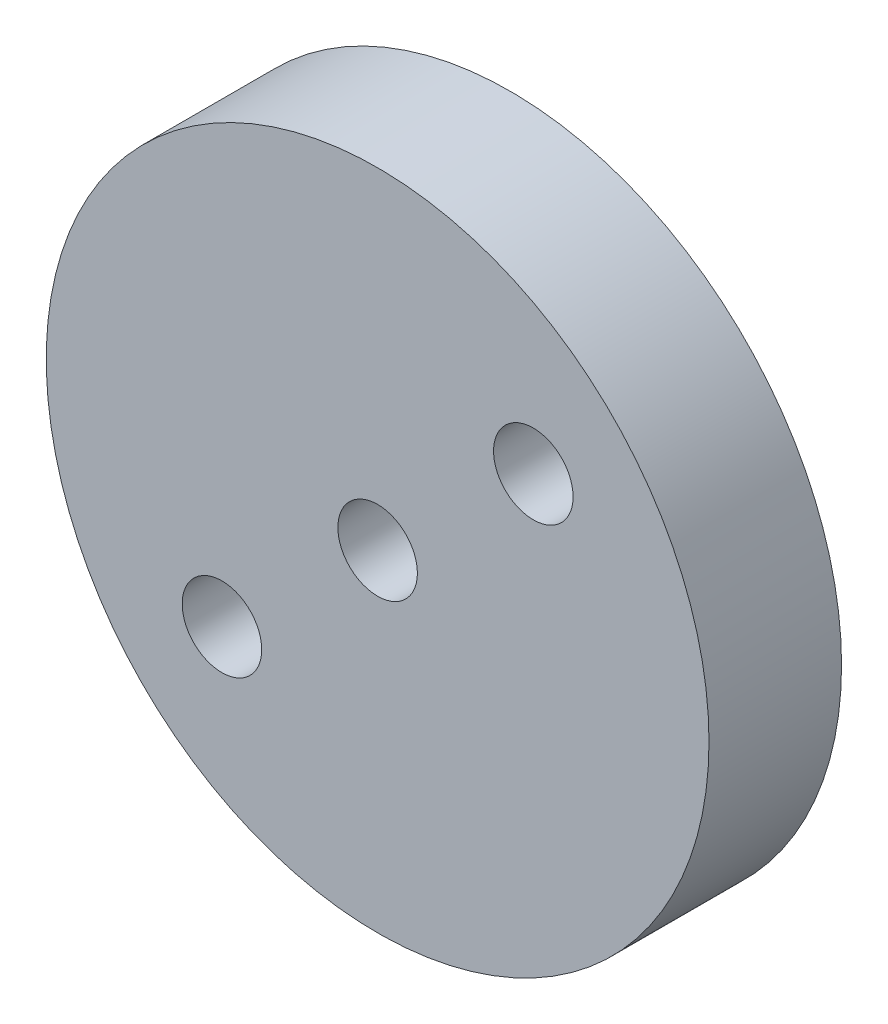
SolidWorks part; units mm, degrees
ref_plane "前视基准面" through (0, 0, 0) normal (0, 0, 1) x (1, 0, 0)
ref_plane "上视基准面" through (0, 0, 0) normal (0, 1, 0) x (1, 0, 0)
ref_plane "右视基准面" through (0, 0, 0) normal (1, 0, 0) x (0, 0, -1)
other "Configuration Table"
sketch "草图1" plane through (0, 0, 0) normal (0, 0, 1) x (1, 0, 0)
  circle A0 centre (0, 0) radius 12.5
  circle A1 centre (0, 0) radius 1.5
  circle A2 centre (-5.8724, -5.4327) radius 1.5
  circle A3 centre (5.8724, 5.4327) radius 1.5
  dimension "D1" = 25
  dimension "D2" = 3
  dimension "D3" = 3
  dimension "D4" = 3
  dimension "D5" = 8
  dimension "D6" = 8
extrude "凸台-拉伸1" add sketch "草图1" along normal blind 5
